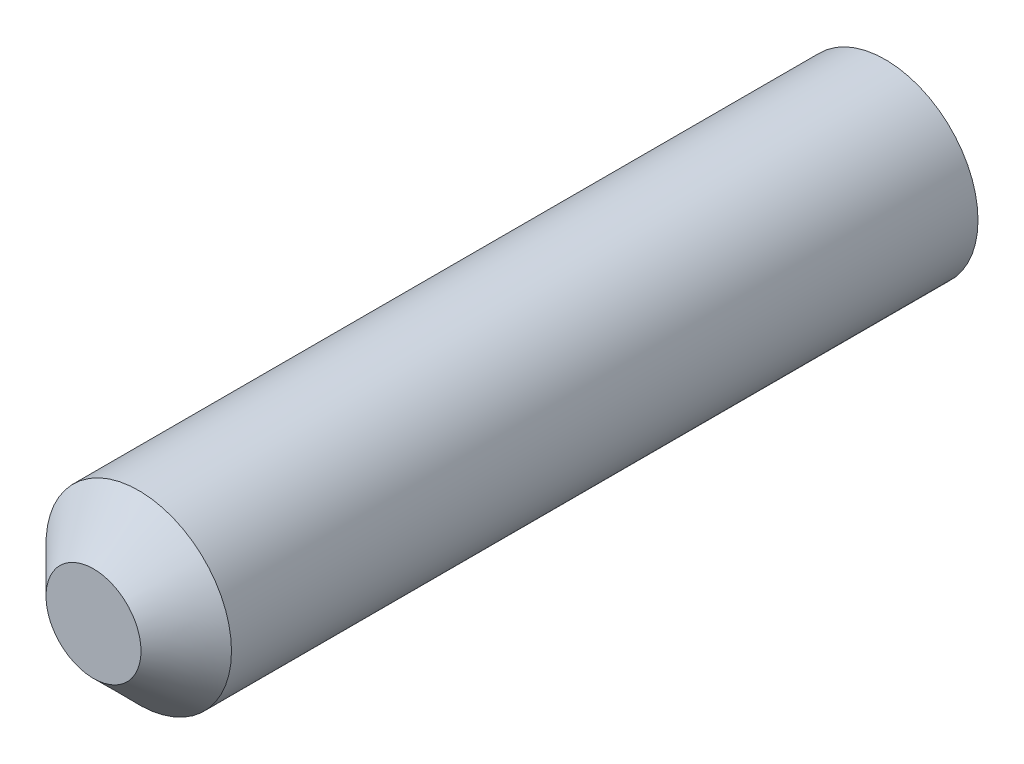
SolidWorks part; units mm, degrees
ref_plane "Piano frontale" through (0, 0, 0) normal (0, 0, 1) x (1, 0, 0)
ref_plane "Piano superiore" through (0, 0, 0) normal (0, 1, 0) x (1, 0, 0)
ref_plane "Piano destro" through (0, 0, 0) normal (1, 0, 0) x (0, 0, -1)
sketch "Schizzo1" plane through (0, 0, 0) normal (0, 0, 1) x (1, 0, 0)
  circle A0 centre (0, 0) radius 2.05
  dimension "D1" = 4.1
extrude "Estrusione-Estrusione1" add sketch "Schizzo1" along normal blind 17.5
chamfer "Smusso1" distance 1 angle 45 1 edges at (2.05, 0, 17.5)
